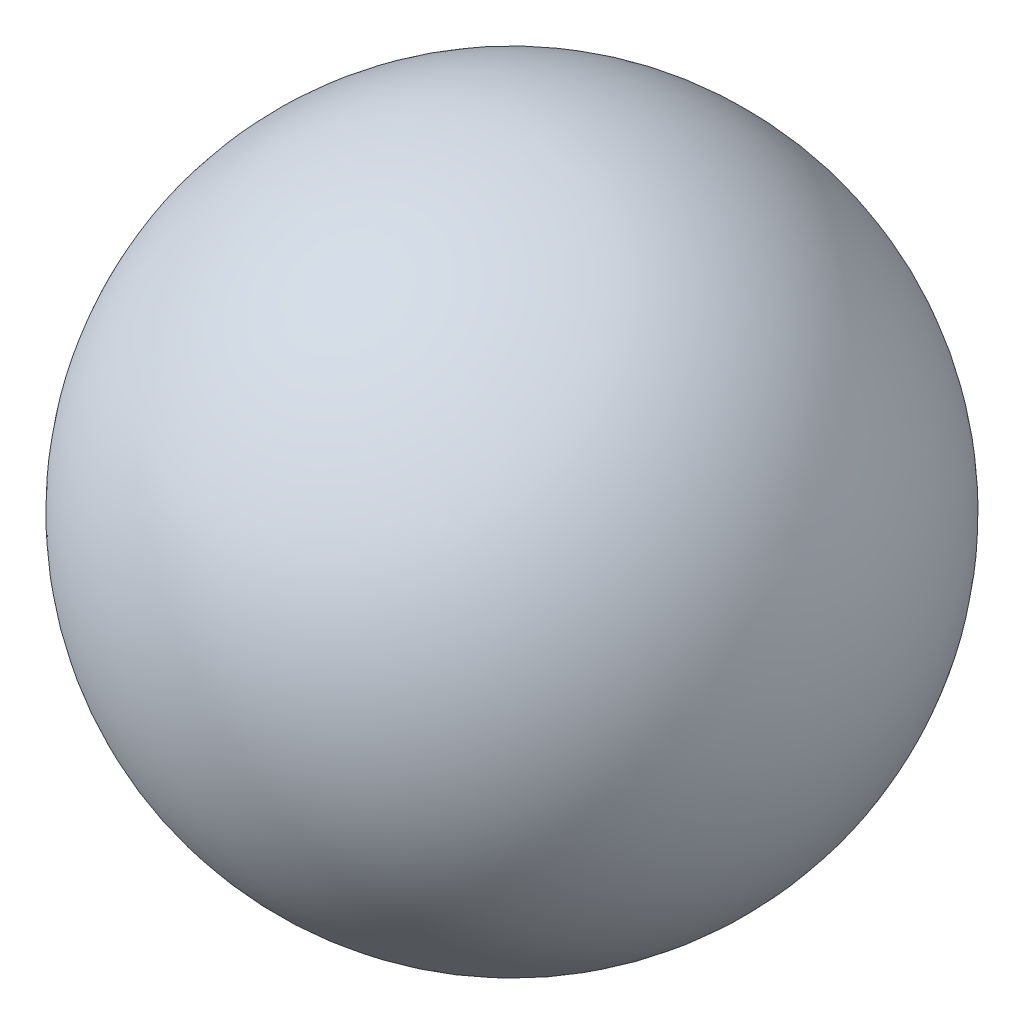
SolidWorks part; units mm, degrees
ref_plane "Front Plane" through (0, 0, 0) normal (0, 0, 1) x (1, 0, 0)
ref_plane "Top Plane" through (0, 0, 0) normal (0, 1, 0) x (1, 0, 0)
ref_plane "Right Plane" through (0, 0, 0) normal (1, 0, 0) x (0, 0, -1)
ref_plane "Plane1"
sketch "Sketch1" plane through (0, 0, 0) normal (0, 0, 1) x (1, 0, 0)
  line L0 (3.6905, 9.75) -> (1.3095, 9.75)
  line L1 (3.6905, 9.75) -> (1.3095, 9.75) construction
  arc A0 (3.6905, 9.75) -> (1.3095, 9.75) centre (2.5, 9.75) ccw
revolve "Revolução1" add sketch "Sketch1" angle 360 about L1
